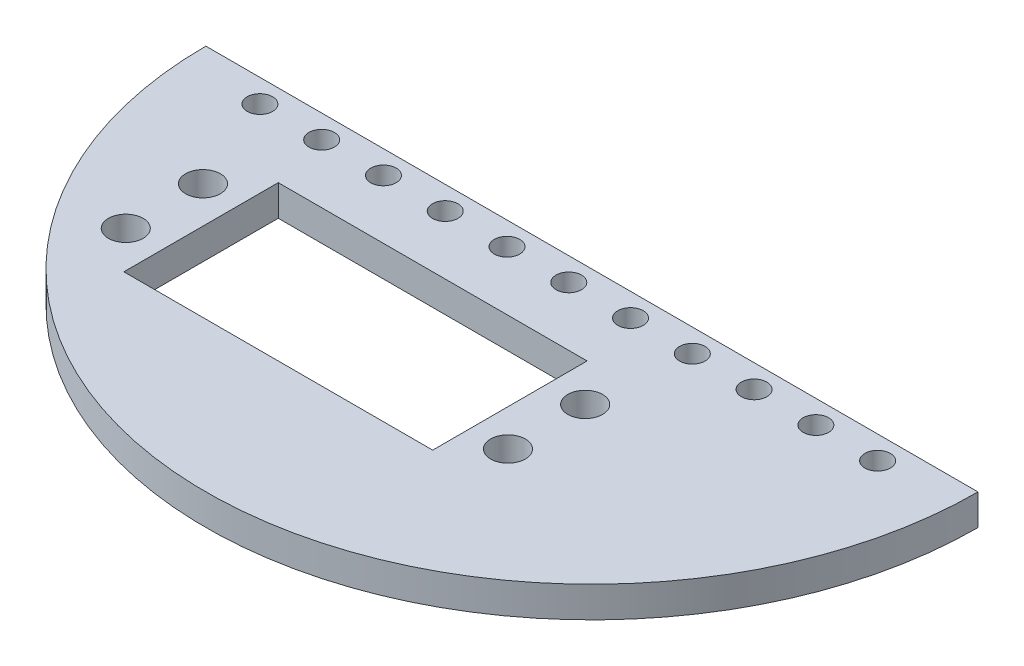
SolidWorks part; units mm, degrees
ref_plane "前视基准面" through (0, 0, 0) normal (0, 0, 1) x (1, 0, 0)
ref_plane "上视基准面" through (0, 0, 0) normal (0, 1, 0) x (1, 0, 0)
ref_plane "右视基准面" through (0, 0, 0) normal (1, 0, 0) x (0, 0, -1)
sketch "草图1" plane through (0, 0, 0) normal (0, 1, 0) x (1, 0, 0)
  line L0 (-50, 0) -> (50, 0)
  arc A0 (50, 0) -> (-50, 0) centre (0, 0) cw
extrude "凸台-拉伸1" add sketch "草图1" along normal blind 4
sketch "草图2" plane through (0, 4, 0) normal (0, 1, 0) x (1, 0, 0)
  line L2 (0, -10.623) -> (10, -10.623)
  line L3 (10, -10.623) -> (10, -30.623)
  line L4 (10, -30.623) -> (-30, -30.623)
  line L5 (-30, -30.623) -> (-30, -10.623)
  line L6 (-30, -10.623) -> (0, -10.623)
extrude "切除-拉伸1" cut sketch "草图2" against normal blind 10
sketch "草图3" plane through (0, 4, 0) normal (0, 1, 0) x (1, 0, 0)
  circle A0 centre (-34.75, -15.623) radius 2.25
  circle A1 centre (-34.75, -25.623) radius 2.25
  circle A2 centre (14.75, -25.623) radius 2.25
  circle A3 centre (14.75, -15.623) radius 2.25
extrude "切除-拉伸2" cut sketch "草图3" against normal blind 10
sketch "草图4" plane through (0, 4, 0) normal (0, 1, 0) x (1, 0, 0)
  circle A0 centre (0, -3) radius 1.65
  circle A1 centre (8, -3) radius 1.65
  circle A2 centre (16, -3) radius 1.65
  circle A3 centre (24, -3) radius 1.65
  circle A4 centre (32, -3) radius 1.65
  circle A5 centre (40, -3) radius 1.65
  circle A6 centre (-40, -3) radius 1.65
  circle A7 centre (-32, -3) radius 1.65
  circle A8 centre (-24, -3) radius 1.65
  circle A9 centre (-16, -3) radius 1.65
  circle A10 centre (-8, -3) radius 1.65
extrude "切除-拉伸3" cut sketch "草图4" against normal blind 10
